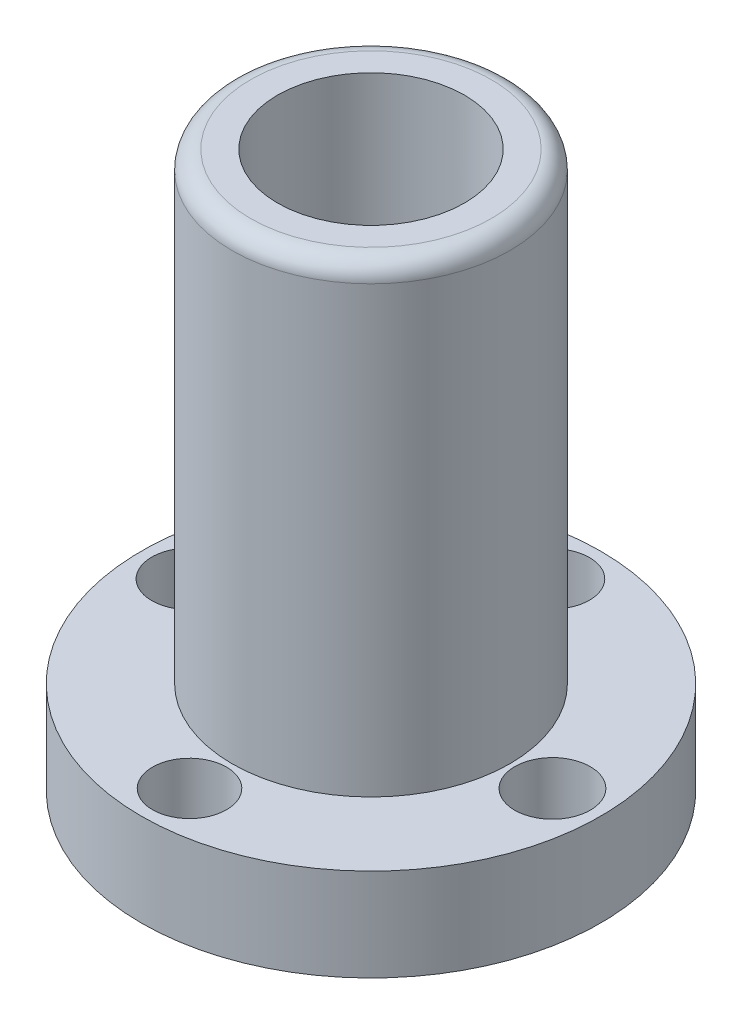
SolidWorks part; units mm, degrees
ref_plane "Front Plane" through (0, 0, 0) normal (0, 0, 1) x (1, 0, 0)
ref_plane "Top Plane" through (0, 0, 0) normal (0, 1, 0) x (1, 0, 0)
ref_plane "Right Plane" through (0, 0, 0) normal (1, 0, 0) x (0, 0, -1)
sketch "Sketch1" plane through (0, 0, 0) normal (0, 1, 0) x (1, 0, 0)
  circle A0 centre (0, 0) radius 19.05
extrude "Boss-Extrude1" add sketch "Sketch1" along normal blind 63.5 contours A0
sketch "Sketch2" plane through (0, 63.5, 0) normal (0, 1, 0) x (1, 0, 0)
  circle A0 centre (0, 0) radius 12.8267
extrude "Cut-Extrude1" cut sketch "Sketch2" against normal through all contours A0
sketch "Sketch3" plane through (0, 0, 0) normal (0, 0, 1) x (1, 0, 0)
  line L0 (-19.05, 31.75) -> (19.05, 31.75)
  line L1 (-19.05, 63.5) -> (-19.05, 0) construction
  line L2 (19.05, 0) -> (19.05, 63.5) construction
  circle A0 centre (0, 31.75) radius 6.3326
extrude "Cut-Extrude2" cut sketch "Sketch3" against normal through all contours A0
fillet "Fillet1" radius 2.54 1 edges at (0, 63.5, 19.05)
sketch "Sketch4" plane through (0, 0, 0) normal (0, -1, 0) x (1, 0, 0)
  circle A0 centre (0, 0) radius 31.496
extrude "Boss-Extrude3" add sketch "Sketch4" along normal blind 12.7
sketch "Sketch5" plane through (0, 0, 0) normal (0, 1, 0) x (1, 0, 0)
  circle A0 centre (0, 24.892) radius 5.0751
  dimension "D1" = 24.892
extrude "Cut-Extrude3" cut sketch "Sketch5" against normal through all
mirror "Mirror1" about plane through (0, 0, 0) normal (1, 0, 0) of "Cut-Extrude3" second plane through (0, 0, 0) second plane normal (0, 0, 1)
sketch "Sketch6" plane through (0, 0, 0) normal (0, 1, 0) x (1, 0, 0)
  circle A0 centre (24.892, 0) radius 5.1829
  dimension "D1" = 24.892
extrude "Cut-Extrude4" cut sketch "Sketch6" against normal through all contours A0
mirror "Mirror2" about plane through (0, 0, 0) normal (0, 0, 1) of "Cut-Extrude4" second plane through (0, 0, 0) second plane normal (1, 0, 0)
